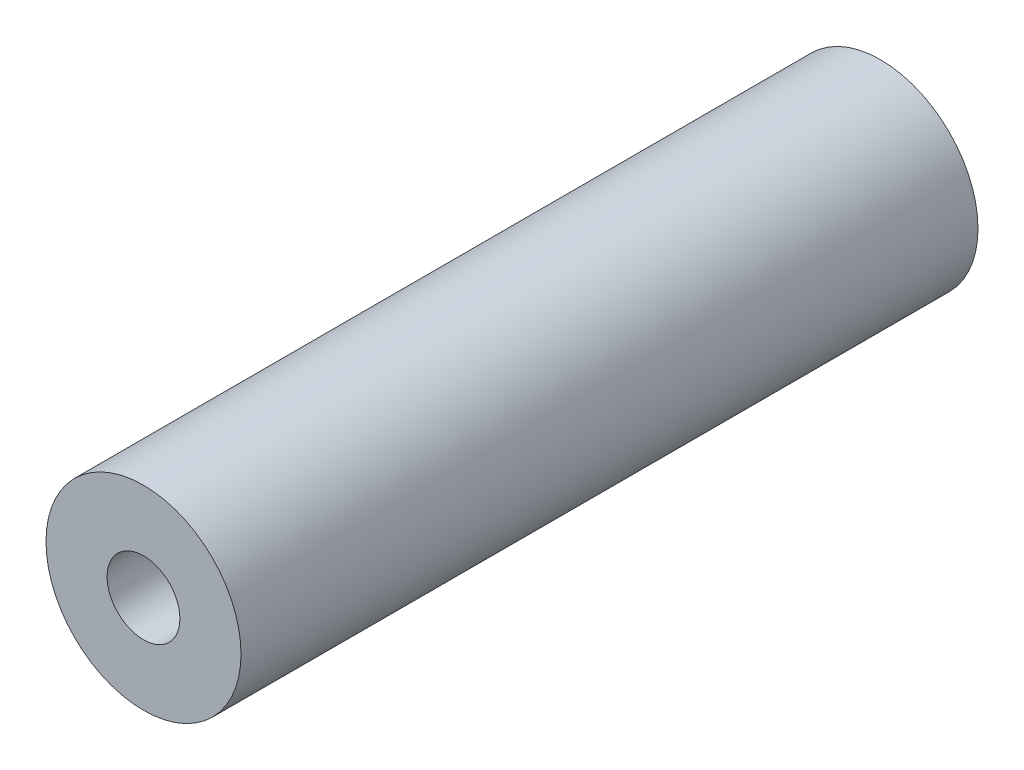
SolidWorks part; units mm, degrees
material "6061-T6 (SS)"
ref_plane "Front Plane" through (0, 0, 0) normal (0, 0, 1) x (1, 0, 0)
ref_plane "Top Plane" through (0, 0, 0) normal (0, 1, 0) x (1, 0, 0)
ref_plane "Right Plane" through (0, 0, 0) normal (1, 0, 0) x (0, 0, -1)
sketch "Sketch1" plane through (0, 0, 0) normal (0, 0, 1) x (1, 0, 0)
  circle A0 centre (0, 0) radius 2.3813
  dimension "D1" = 4.7625
extrude "Boss-Extrude1" add sketch "Sketch1" along normal blind 18
hole_wizard "#2-56 Tapped Hole1" positions "Sketch3" profile "Sketch2" tap size "#2-56" standard "ANSI Inch" end condition through all
sketch "Sketch3" plane through (0, 0, 18) normal (0, 0, 1) x (1, 0, 0)
  point P0 (0, 0)
sketch "Sketch2" plane through (0, 0, 18) normal (1, 0, 0) x (0, -1, 0)
  line L0 (0, 0) -> (0, 18)
  line L1 (0, 18) -> (0.889, 18)
  line L2 (0.889, 18) -> (0.889, 0)
  line L5 (0.889, 0) -> (0, 0)
  line L11 (0, -6.35) -> (0, 107.95) construction
  dimension "Thru Tap Drill Dia." = 1.778
  dimension "Thru Tap Drill Depth" = 18
cosmetic thread "Hole Thread1" parameters "D2"=2.1844
